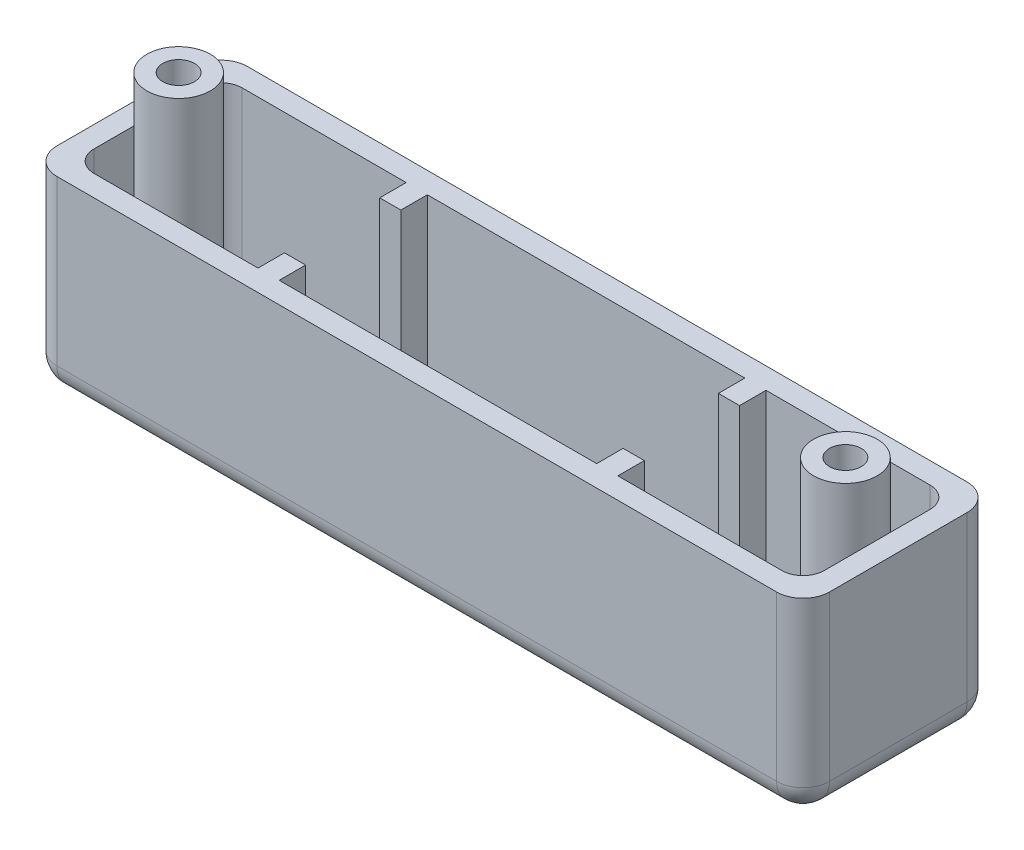
SolidWorks part; units mm, degrees
ref_plane "Front Plane" through (0, 0, 0) normal (0, 0, 1) x (1, 0, 0)
ref_plane "Top Plane" through (0, 0, 0) normal (0, 1, 0) x (1, 0, 0)
ref_plane "Right Plane" through (0, 0, 0) normal (1, 0, 0) x (0, 0, -1)
sketch "Sketch1" plane through (0, 0, 0) normal (0, 1, 0) x (1, 0, 0)
  line L1 (-18.542, -4.572) -> (18.542, -4.572)
  line L2 (-18.542, -4.572) -> (-18.542, 4.572)
  line L3 (-18.542, 4.572) -> (18.542, 4.572)
  line L4 (18.542, -4.572) -> (18.542, 4.572)
  line L5 (-18.542, -4.572) -> (18.542, 4.572) construction
  line L6 (-18.542, 4.572) -> (18.542, -4.572) construction
  point P0 (0, 0)
  dimension "D1" = 37.084
  dimension "D2" = 9.144
extrude "Boss-Extrude1" add sketch "Sketch1" along normal blind 9.144
sketch "Sketch2" plane through (0, 9.144, 0) normal (0, 1, 0) x (1, 0, 0)
  line L0 (-18.542, 4.572) -> (-18.542, -4.572) construction
  line L1 (-17.526, 3.556) -> (17.526, 3.556)
  line L2 (-17.526, 3.556) -> (-17.526, -3.556)
  line L3 (-17.526, -3.556) -> (17.526, -3.556)
  line L4 (17.526, 3.556) -> (17.526, -3.556)
  line L5 (-17.526, 3.556) -> (17.526, -3.556) construction
  line L6 (-17.526, -3.556) -> (17.526, 3.556) construction
  line L7 (-18.542, -4.572) -> (18.542, -4.572) construction
  point P0 (0, 0)
  dimension "D1" = 1.016
  dimension "D2" = 1.016
extrude "Cut-Extrude3" cut sketch "Sketch2" against normal offset from surface (7.493 mm away) 1.651 up to face at (0, 0, 0)
fillet "Fillet1" radius 1.27 8 edges at (18.542, 0, 0) (18.542, 4.572, -4.572) (0, 0, -4.572) (0, 0, 4.572) (-18.542, 0, 0) (-18.542, 4.572, -4.572) (-18.542, 4.572, 4.572) (18.542, 4.572, 4.572)
fillet "Fillet2" radius 1.016 4 edges at (17.526, 5.3975, 3.556) (17.526, 5.3975, -3.556) (-17.526, 5.3975, 3.556) (-17.526, 5.3975, -3.556)
sketch "Sketch10" plane through (0, 1.651, 0) normal (0, 1, 0) x (1, 0, 0)
  line L6 (16.51, 3.556) -> (-16.51, 3.556) construction
  line L7 (-8.636, 3.556) -> (-7.62, 3.556)
  line L8 (-8.636, 3.556) -> (-8.636, 2.286)
  line L9 (-8.636, 2.286) -> (-7.62, 2.286)
  line L10 (-7.62, 3.556) -> (-7.62, 2.286)
  line L11 (7.62, 3.556) -> (8.636, 3.556)
  line L12 (7.62, 3.556) -> (7.62, 2.286)
  line L13 (7.62, 2.286) -> (8.636, 2.286)
  line L14 (8.636, 3.556) -> (8.636, 2.286)
  line L15 (-8.636, -2.286) -> (-7.62, -2.286)
  line L16 (-8.636, -2.286) -> (-8.636, -3.556)
  line L17 (-8.636, -3.556) -> (-7.62, -3.556)
  line L18 (-7.62, -2.286) -> (-7.62, -3.556)
  line L19 (7.62, -2.286) -> (8.636, -2.286)
  line L20 (7.62, -2.286) -> (7.62, -3.556)
  line L21 (7.62, -3.556) -> (8.636, -3.556)
  line L22 (8.636, -2.286) -> (8.636, -3.556)
  line L23 (-16.51, -3.556) -> (16.51, -3.556) construction
  line L24 (-19.5834, 0) -> (19.5834, 0) construction
  line L25 (0, 0) -> (0, 13.384) construction
  dimension "D8" = 1.27
  dimension "D9" = 1.016
  dimension "D10" = 15.24
extrude "Boss-Extrude5" add sketch "Sketch10" along normal up to surface (7.493 mm away) up to face at (0, 9.144, 0)
sketch "Sketch11" plane through (0, 1.651, 0) normal (0, 1, 0) x (1, 0, 0)
  line L0 (-17.526, 0) -> (17.526, 0) construction
  line L1 (17.526, -2.54) -> (17.526, 2.54) construction
  line L2 (-17.526, 2.54) -> (-17.526, -2.54) construction
  line L4 (0, 0) -> (0, -9.0572) construction
  line L7 (-17.526, 2.54) -> (-17.526, -2.54) construction
  circle A2 centre (16.002, 0) radius 1.524
  circle A3 centre (-16.002, 0) radius 1.524
  dimension "D1" = 3.048
extrude "Boss-Extrude8" add sketch "Sketch11" along normal blind 10.16 separate body
sketch "Sketch12" plane through (0, 11.811, 0) normal (0, 1, 0) x (1, 0, 0)
  circle A0 centre (-16.002, 0) radius 0.762
  circle A1 centre (16.002, 0) radius 0.762
  circle A3 centre (16.002, 0) radius 1.524 construction
  circle A5 centre (-16.002, 0) radius 1.524 construction
  dimension "D1" = 1.524
extrude "Cut-Extrude4" cut sketch "Sketch12" against normal blind 5.08
